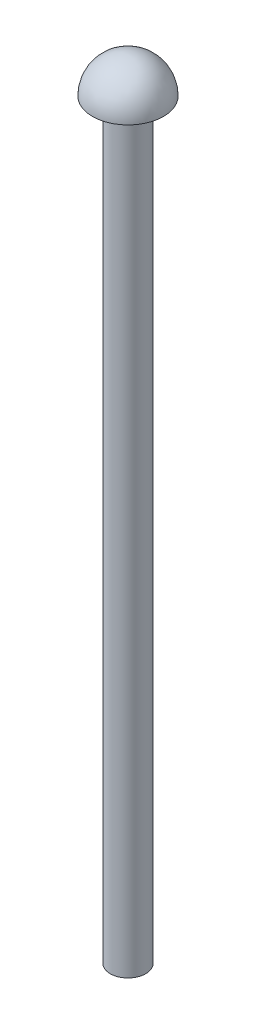
SolidWorks part; units mm, degrees
ref_plane "Front Plane" through (0, 0, 0) normal (0, 0, 1) x (1, 0, 0)
ref_plane "Top Plane" through (0, 0, 0) normal (0, 1, 0) x (1, 0, 0)
ref_plane "Right Plane" through (0, 0, 0) normal (1, 0, 0) x (0, 0, -1)
sketch "Sketch1" plane through (0, 0, 0) normal (0, 1, 0) x (1, 0, 0)
  circle A0 centre (0, 0) radius 1.5
  dimension "D1" = 3
extrude "Boss-Extrude1" add sketch "Sketch1" along normal blind 63.5
sketch "Sketch4" plane through (0, 63.5, 0) normal (0, 1, 0) x (1, 0, 0)
  line L0 (0, 3) -> (0, -3)
  circle A0 centre (0, 0) radius 3
revolve "Revolve1" add sketch "Sketch4" angle 180 about L0
